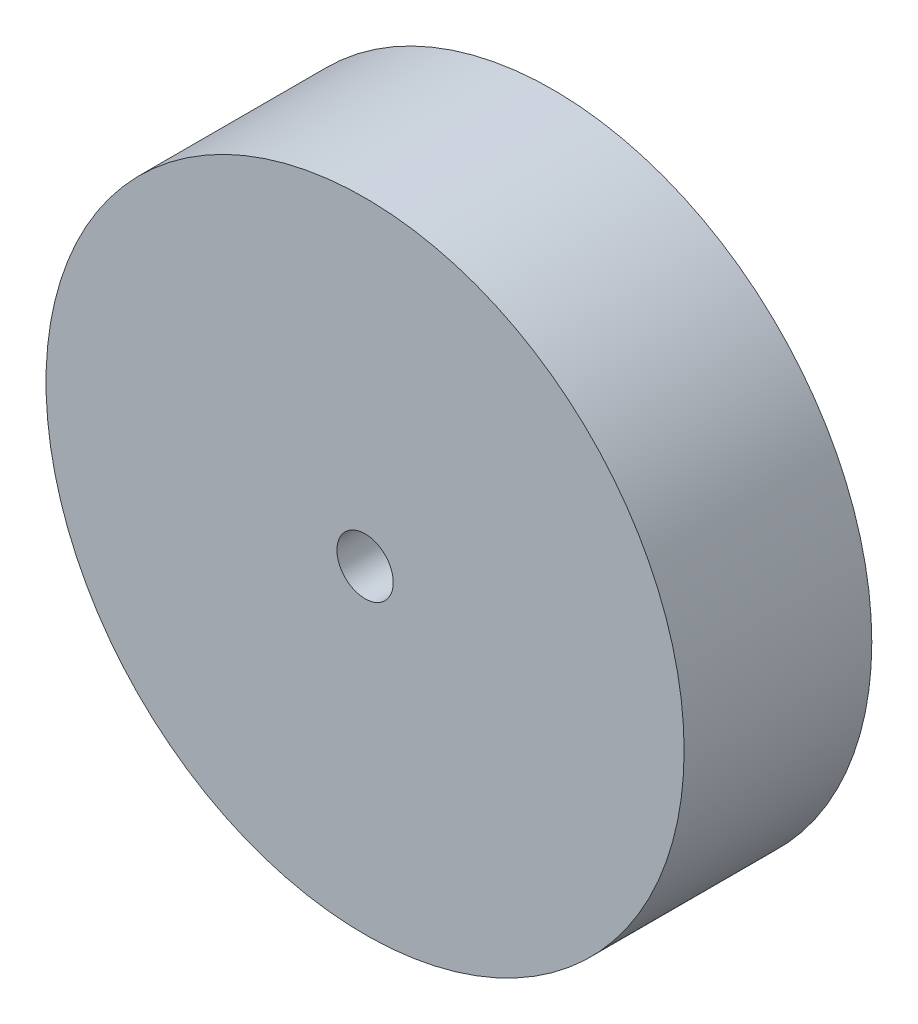
SolidWorks part; units mm, degrees
ref_plane "Front Plane" through (0, 0, 0) normal (0, 0, 1) x (1, 0, 0)
ref_plane "Top Plane" through (0, 0, 0) normal (0, 1, 0) x (1, 0, 0)
ref_plane "Right Plane" through (0, 0, 0) normal (1, 0, 0) x (0, 0, -1)
sketch "Sketch1" plane through (0, 0, 0) normal (0, 0, 1) x (1, 0, 0)
  circle A0 centre (0, 0) radius 1.5
  circle A1 centre (0, 0) radius 17
  dimension "D1" = 34
  dimension "D2" = 3
extrude "Boss-Extrude1" add sketch "Sketch1" along normal blind 10
